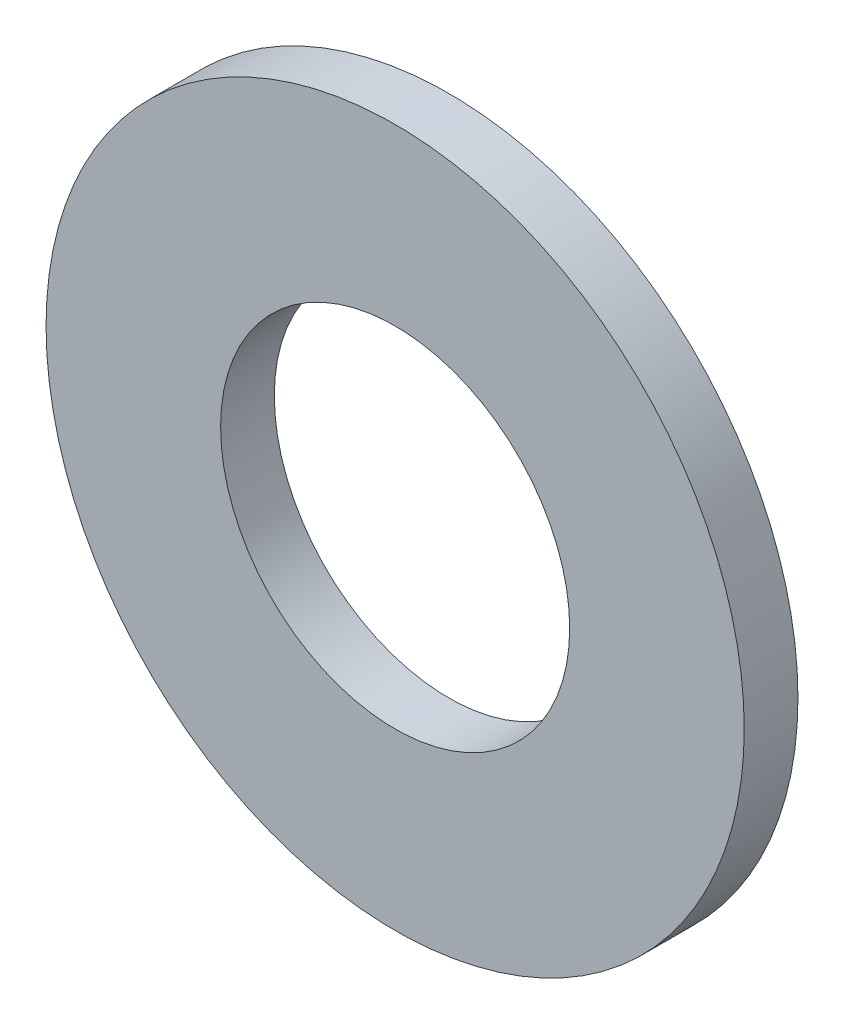
SolidWorks part; units mm, degrees
material "炭素鋼(普通)"
ref_plane "正面" through (0, 0, 0) normal (0, 0, 1) x (1, 0, 0)
ref_plane "平面" through (0, 0, 0) normal (0, 1, 0) x (1, 0, 0)
ref_plane "右側面" through (0, 0, 0) normal (1, 0, 0) x (0, 0, -1)
sketch "ｽｹｯﾁ1" plane through (0, 0, 0) normal (0, 0, 1) x (1, 0, 0)
  circle A0 centre (0, 0) radius 3.25
  circle A1 centre (0, 0) radius 6.5
  dimension "D1" = 6.5
  dimension "D2" = 13
extrude "ﾎﾞｽ - 押し出し1" add sketch "ｽｹｯﾁ1" along normal blind 1
